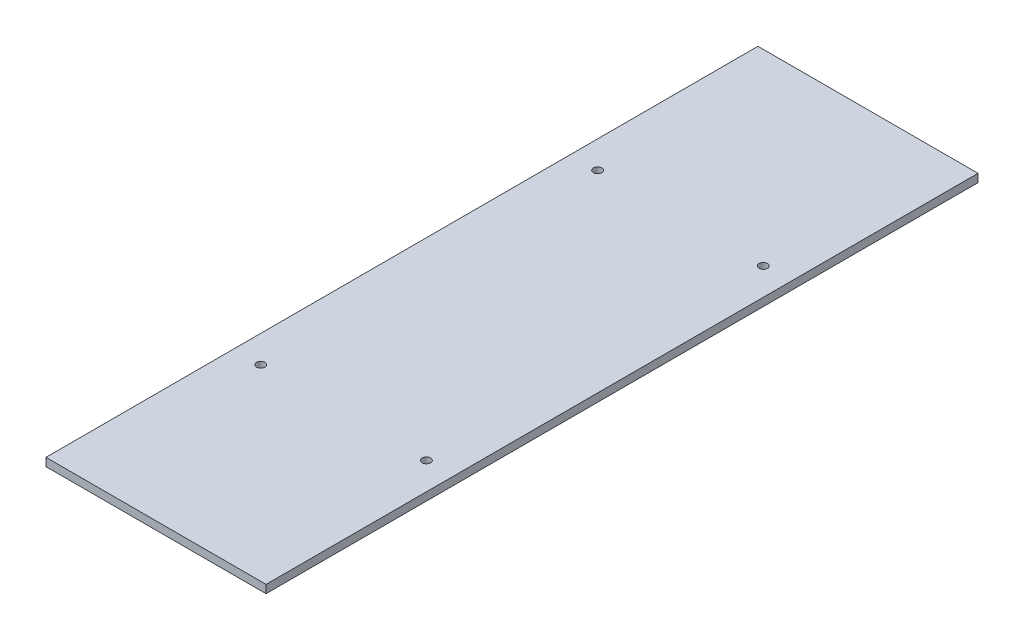
SolidWorks part; units mm, degrees
ref_plane "Front Plane" through (0, 0, 0) normal (0, 0, 1) x (1, 0, 0)
ref_plane "Top Plane" through (0, 0, 0) normal (0, 1, 0) x (1, 0, 0)
ref_plane "Right Plane" through (0, 0, 0) normal (1, 0, 0) x (0, 0, -1)
sketch "Sketch1" plane through (0, 0, 0) normal (0, 1, 0) x (1, 0, 0)
  line L0 (0, 139.7) -> (0, -139.7) construction
  line L1 (-43.175, 139.7) -> (43.175, 139.7)
  line L2 (-43.175, 139.7) -> (-43.175, -139.7)
  line L3 (-43.175, -139.7) -> (43.175, -139.7)
  line L4 (43.175, 139.7) -> (43.175, -139.7)
  line L5 (-43.175, 139.7) -> (43.175, -139.7) construction
  line L6 (-43.175, -139.7) -> (43.175, 139.7) construction
  line L7 (-32.5, 132.2) -> (32.5, 132.2) construction
  line L8 (-32.5, 132.2) -> (-32.5, -132.2) construction
  line L9 (-32.5, -132.2) -> (32.5, -132.2) construction
  line L10 (32.5, 132.2) -> (32.5, -132.2) construction
  line L11 (-32.5, 132.2) -> (32.5, -132.2) construction
  line L12 (-32.5, -132.2) -> (32.5, 132.2) construction
  line L13 (-43.175, 0) -> (43.175, 0) construction
  line L14 (-32.5, -132.2) -> (32.5, -132.2) construction
  line L15 (-32.5, 66.1) -> (-32.5, 0) construction
  line L16 (-32.5, 66.1) -> (-32.5, 132.2) construction
  circle A12 centre (-32.5, 66.1) radius 1.65
  circle A13 centre (32.5, 66.1) radius 1.65
  circle A14 centre (32.5, -66.1) radius 1.65
  circle A15 centre (-32.5, -66.1) radius 1.65
  point P0 (0, 0)
  point P6 (0, 0)
  dimension "D5" = 3.3
  dimension "D1" = 7.5
  dimension "D2" = 10.675
  dimension "D3" = 279.4
  dimension "D4" = 86.35
extrude "Boss-Extrude1" add sketch "Sketch1" along normal blind 3.175
